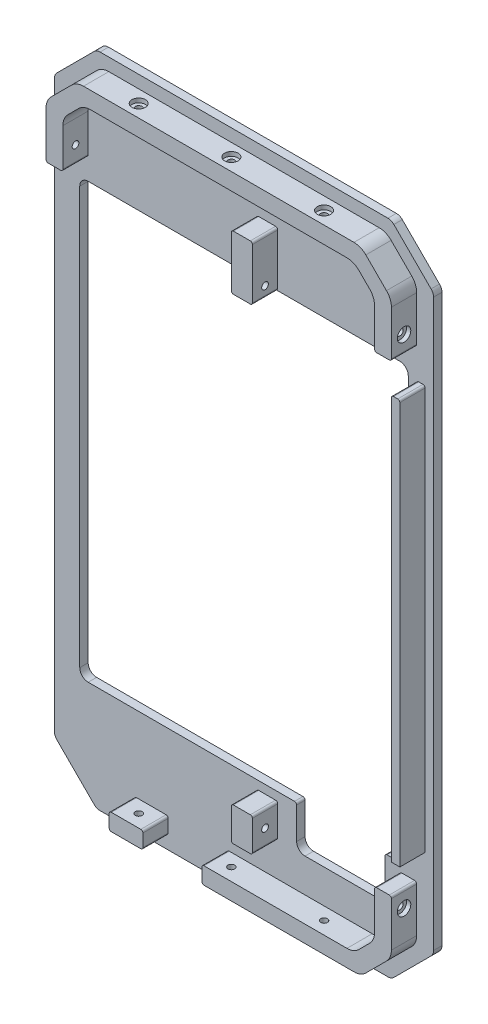
SolidWorks part; units mm, degrees
material "6061-T4 (SS)"
ref_plane "前视基准面" through (0, 0, 0) normal (0, 0, 1) x (1, 0, 0)
ref_plane "上视基准面" through (0, 0, 0) normal (0, 1, 0) x (1, 0, 0)
ref_plane "右视基准面" through (0, 0, 0) normal (1, 0, 0) x (0, 0, -1)
sketch "草图1" plane through (0, 0, 0) normal (0, 0, 1) x (1, 0, 0)
  line L1 (0, 0) -> (-90, 0)
  line L2 (0, 0) -> (0, 156)
  line L3 (0, 156) -> (-90, 156)
  line L4 (-90, 0) -> (-90, 156)
  dimension "D1" = 90
  dimension "D2" = 156
extrude "凸台-拉伸1" add sketch "草图1" along normal blind 2
chamfer "倒角1" distance 10 angle 45 4 edges at (0, 0, 1) (-90, 0, 1) (-90, 156, 1) (0, 156, 1)
sketch "草图2" plane through (0, 0, 2) normal (0, 0, 1) x (1, 0, 0)
  line L0 (-10, 156) -> (-80, 156) construction
  line L1 (-78.7574, 153) -> (-11.2426, 153)
  line L2 (-87, 144.7574) -> (-87, 11.2426)
  line L3 (-78.7574, 3) -> (-11.2426, 3)
  line L4 (-3, 144.7574) -> (-3, 11.2426)
  line L5 (-80, 0) -> (-10, 0) construction
  line L6 (-90, 146) -> (-90, 10) construction
  line L7 (0, 10) -> (0, 146) construction
  line L8 (-87, 144.7574) -> (-78.7574, 153)
  line L10 (-11.2426, 153) -> (-3, 144.7574)
  line L11 (-85, 151) -> (-82.8787, 148.8787) construction
  line L12 (-87, 11.2426) -> (-78.7574, 3)
  line L14 (-3, 11.2426) -> (-11.2426, 3)
  line L17 (-80, 156) -> (-90, 146) construction
  line L18 (-5, 151) -> (-7.1213, 148.8787) construction
  line L19 (0, 146) -> (-10, 156) construction
  line L20 (-85, 5) -> (-82.8787, 7.1213) construction
  line L21 (-90, 10) -> (-80, 0) construction
  line L22 (-5, 5) -> (-7.1213, 7.1213) construction
  line L24 (-10, 0) -> (0, 10) construction
  dimension "D1" = 3
  dimension "D2" = 3
  dimension "D3" = 3
  dimension "D4" = 3
  dimension "D5" = 3
  dimension "D6" = 3
  dimension "D7" = 3
  dimension "D8" = 3
extrude "凸台-拉伸2" add sketch "草图2" along normal blind 6
sketch "草图4" plane through (-87, 0, 0) normal (-1, 0, 0) x (0, 0, 1)
  line L2 (0, 156) -> (2, 156) construction
  line L3 (2, 0) -> (0, 0) construction
  line L4 (5, 11.2426) -> (5, 144.7574) construction
  line L5 (8, 11.2426) -> (2, 11.2426) construction
  line L6 (8, 144.7574) -> (2, 144.7574) construction
  circle A0 centre (5, 137) radius 0.8
  circle A1 centre (5, 19) radius 0.8
  point P10 (1, 0)
  dimension "D3" = 19
  dimension "D2" = 19
shell "抽壳3" thickness 4
sketch "草图5" plane through (0, 3, 0) normal (0, -1, 0) x (-1, 0, 0)
  line L0 (45, -5) -> (45, -8) construction
  line L1 (78.7574, -8) -> (11.2426, -8) construction
  circle A1 centre (67, -5) radius 0.8
  circle A2 centre (23, -5) radius 0.8
  circle A3 centre (45, -5) radius 0.8
  dimension "D1" = 22
  dimension "D2" = 22
extrude "上下盖子孔" cut sketch "草图5" against normal blind 200
sketch "草图25" plane through (0, 0, 8) normal (0, 0, 1) x (1, 0, 0)
  line L0 (-87, 144.7574) -> (-87, 11.2426) construction
  line L1 (-101.5211, 153.7054) -> (-86, 153.7054)
  line L2 (-101.5211, 153.7054) -> (-101.5211, -12.2357)
  line L3 (-101.5211, -12.2357) -> (-86, -12.2357)
  line L4 (-86, 153.7054) -> (-86, -12.2357)
  line L5 (-3, 11.2426) -> (-3, 144.7574) construction
  line L6 (30.0437, 153.7054) -> (-4, 153.7054)
  line L7 (30.0437, 153.7054) -> (30.0437, -12.2357)
  line L8 (30.0437, -12.2357) -> (-4, -12.2357)
  line L9 (-4, 153.7054) -> (-4, -12.2357)
  dimension "D1" = 1
  dimension "D2" = 1
extrude "切除-拉伸17" cut sketch "草图25" against normal blind 6
sketch "草图8" plane through (0, 0, 8) normal (0, 0, 1) x (1, 0, 0)
  line L0 (-10, 156) -> (-80, 156) construction
  line L5 (-100.9873, 133) -> (8.5404, 133)
  line L12 (-100.9873, 133) -> (-100.9873, 23)
  line L13 (-100.9873, 23) -> (8.5404, 23)
  line L14 (8.5404, 133) -> (8.5404, 23)
  line L15 (-80, 0) -> (-10, 0) construction
  dimension "D1" = 23
  dimension "D2" = 23
extrude "刀路" cut sketch "草图8" against normal blind 6
sketch "草图28" plane through (0, 0, 2) normal (0, 0, 1) x (1, 0, 0)
  line L0 (-82, 143.1005) -> (-82, 144.1005)
  line L2 (-83, 143.1005) -> (-83, 133)
  line L3 (-83, 133) -> (-82, 133)
  line L4 (-82, 143.1005) -> (-82, 133)
  line L5 (-83, 143.1005) -> (-77.1005, 149) construction
  line L6 (-82, 144.1005) -> (-83, 143.1005)
  line L7 (-8, 143.1005) -> (-8, 144.1005)
  line L8 (-7, 133) -> (-8, 133)
  line L9 (-7, 133) -> (-7, 143.1005)
  line L11 (-8, 133) -> (-8, 143.1005)
  line L12 (-12.8995, 149) -> (-7, 143.1005) construction
  line L13 (-8, 144.1005) -> (-7, 143.1005)
  line L14 (-8, 12.8995) -> (-8, 11.8995)
  line L16 (-7, 12.8995) -> (-7, 23)
  line L17 (-7, 23) -> (-8, 23)
  line L18 (-8, 12.8995) -> (-8, 23)
  line L19 (-7, 12.8995) -> (-12.8995, 7) construction
  line L20 (-8, 11.8995) -> (-7, 12.8995)
extrude "凸台-拉伸5" add sketch "草图28" along normal blind 6
fillet "外角" radius 2 8 edges at (0, 10, 1) (-10, 0, 1) (-80, 0, 1) (-90, 10, 1) (-90, 146, 1) (-80, 156, 1) (0, 146, 1) (-10, 156, 1)
fillet "外内角" radius 4 16 edges at (-78.7574, 3, 5) (-11.2426, 3, 5) (-11.2426, 153, 5) (-78.7574, 153, 5) (-86, 10.2426, 5) (-4, 10.2426, 5) (-4, 145.7574, 5) (-86, 145.7574, 5) (-77.1005, 7, 5) (-83, 12.8995, 5) (-12.8995, 7, 5) (-8, 11.8995, 5) (-8, 144.1005, 5) (-12.8995, 149, 5) (-77.1005, 149, 5) (-82, 144.1005, 5)
extrude "盖子孔" cut sketch "草图4" against normal blind 100
sketch "草图6" plane through (0, 0, 2) normal (0, 0, 1) x (1, 0, 0)
  line L0 (-90, 145.1716) -> (-90, 10.8284) construction
  line L5 (-79.1716, 0) -> (-10.8284, 0) construction
  line L10 (-10.8284, 156) -> (-79.1716, 156) construction
  line L17 (-42, 141) -> (-37, 141)
  line L18 (-42, 141) -> (-42, 128)
  line L19 (-42, 15) -> (-37, 15)
  line L20 (-37, 141) -> (-37, 128)
  line L25 (-42, 23) -> (-42, 15)
  line L26 (-42, 128) -> (-37, 128)
  line L28 (-42, 23) -> (-37, 23)
  line L30 (-37, 23) -> (-37, 15)
  dimension "D1" = 48
  dimension "D2" = 5
  dimension "D3" = 15
  dimension "D4" = 15
  dimension "D5" = 13
  dimension "D6" = 8
extrude "凸台-拉伸3" add sketch "草图6" along normal blind 6
sketch "草图17" plane through (-37, 0, 0) normal (1, 0, 0) x (0, 0, -1)
  line L0 (-5, 23) -> (-5, 15) construction
  line L1 (-8, 15) -> (-2, 15) construction
  line L2 (-8, 128) -> (-2, 128) construction
  line L3 (-8, 23) -> (-2, 23) construction
  circle A0 centre (-5, 130.5) radius 0.8
  circle A1 centre (-5, 19) radius 0.8
  dimension "D1" = 2.5
extrude "主板螺孔" cut sketch "草图17" against normal blind 10
sketch "草图10" plane through (0, 0, 8) normal (0, 0, 1) x (1, 0, 0)
  line L0 (-42, 128) -> (-37, 128) construction
  line L10 (-37, 23) -> (-42, 23) construction
  line L16 (0, 10.8284) -> (0, 145.1716) construction
  line L22 (-84, 128) -> (-6, 128)
  line L23 (-84, 128) -> (-84, 25)
  line L25 (-84, 25) -> (-6, 25)
  line L26 (-6, 128) -> (-6, 25)
  line L27 (-90, 145.1716) -> (-90, 10.8284) construction
  dimension "D1" = 6
  dimension "D2" = 6
  dimension "D3" = 2
  dimension "D4" = 0
sketch "草图11" plane through (0, 0, 8) normal (0, 0, 1) x (1, 0, 0)
  line L12 (-63, 15.8854) -> (-49, 15.8854)
  line L13 (-63, 15.8854) -> (-63, -3.0549)
  line L14 (-63, -3.0549) -> (-49, -3.0549)
  line L15 (-49, 15.8854) -> (-49, -3.0549)
  line L50 (-90, 145.1716) -> (-90, 10.8284) construction
  line L56 (-90, 33.7511) -> (-71, 33.7511)
  line L57 (-90, 33.7511) -> (-90, -5.4069)
  line L58 (-90, -5.4069) -> (-71, -5.4069)
  line L59 (-71, 33.7511) -> (-71, -5.4069)
  dimension "D1" = 8
extrude "PCI-E" cut sketch "草图11" against normal blind 6
sketch "草图14" plane through (0, 0, 0) normal (0, 0, -1) x (-1, 0, 0)
  line L0 (0, 10.8284) -> (0, 145.1716) construction
  line L1 (27, 10) -> (63, 10) construction
  line L2 (27, 10) -> (27, 146) construction
  line L3 (27, 146) -> (63, 146) construction
  line L4 (63, 10) -> (63, 146) construction
  line L5 (79.1716, 0) -> (10.8284, 0) construction
  line L6 (90, 145.1716) -> (90, 10.8284) construction
  line L7 (10.8284, 156) -> (79.1716, 156) construction
  circle A0 centre (27, 10) radius 1
  circle A1 centre (63, 10) radius 1
  circle A2 centre (27, 146) radius 1
  circle A3 centre (63, 146) radius 1
  dimension "D1" = 27
  dimension "D2" = 10
  dimension "D3" = 27
  dimension "D4" = 10
extrude "IO螺孔" [suppressed] cut sketch "草图14" against normal blind 10
extrude "IO挖空" cut sketch "草图10" against normal blind 10
sketch "草图15" plane through (0, 0, 0) normal (0, 0, -1) x (-1, 0, 0)
  line L0 (6, 25) -> (6, 128) construction
  line L5 (11.5, 25) -> (32.5, 25)
  line L6 (11.5, 25) -> (11.5, 15)
  line L8 (32.5, 25) -> (32.5, 15)
  line L11 (11.5, 15) -> (32.5, 15)
  line L12 (84, 25) -> (6, 25) construction
  dimension "D1" = 10
  dimension "D2" = 21
  dimension "D3" = 0
  dimension "D4" = 5.5
extrude "电源挖空" cut sketch "草图15" against normal blind 10
fillet "圆角3" [suppressed] radius 1
hole_wizard "打孔尺寸(%根据)内六角花形沉头螺钉的类型1" [suppressed] positions "草图18" profile "草图19" countersink size "M6" standard "GB"
sketch "草图18" [suppressed] plane through (0, 0, 0) normal (0, 0, -1) x (-1, 0, 0)
  point P0 (27, 146)
  point P3 (63, 146)
  point P6 (27, 10)
  point P9 (63, 10)
sketch "草图19" plane through (-27, 146, 0) normal (1, 0, 0) x (0, 1, 0)
  line L0 (0, 0) -> (0, 8)
  line L1 (0, 8) -> (1.1, 8)
  line L2 (1.1, 8) -> (1.1, 1.1)
  line L3 (1.1, 1.1) -> (2.2, 0)
  line L5 (2.2, 0) -> (0, 0)
  line L6 (-1.1, 1.1) -> (-2.2, 0) construction
  line L11 (0, -6.35) -> (0, 107.95) construction
  dimension "通孔孔直径" = 2.2
  dimension "通孔孔深度" = 8
  dimension "近端锥形沉头孔直径" = 4.4
  dimension "近端锥形沉头孔角度" = 90
sketch "草图21" plane through (0, 3, 0) normal (0, -1, 0) x (-1, 0, 0)
  circle A0 centre (67, -5) radius 1.6
  circle A1 centre (45, -5) radius 1.6
  circle A2 centre (23, -5) radius 1.6
extrude "切除-拉伸14" cut sketch "草图21" against normal blind 1
sketch "草图20" plane through (0, 153, 0) normal (0, 1, 0) x (1, 0, 0)
  circle A0 centre (-67, -5) radius 1.6
  circle A1 centre (-45, -5) radius 1.6
  circle A2 centre (-23, -5) radius 1.6
extrude "螺孔装饰" cut sketch "草图20" against normal blind 1
sketch "草图22" plane through (-86, 0, 0) normal (-1, 0, 0) x (0, 0, 1)
  circle A0 centre (5, 137) radius 1.6
  circle A1 centre (5, 19) radius 1.6
extrude "切除-拉伸15" cut sketch "草图22" against normal blind 1
sketch "草图23" plane through (-4, 0, 0) normal (1, 0, 0) x (0, 0, -1)
  circle A0 centre (-5, 137) radius 1.6
  circle A1 centre (-5, 19) radius 1.6
extrude "切除-拉伸16" cut sketch "草图23" against normal blind 1
sketch "草图26" plane through (0, 0, 2) normal (0, 0, 1) x (1, 0, 0)
  line L0 (0, 10.8284) -> (0, 145.1716) construction
  line L1 (-4, 126) -> (-2, 126)
  line L2 (-4, 126) -> (-4, 30)
  line L3 (-4, 30) -> (-2, 30)
  line L4 (-2, 126) -> (-2, 30)
  line L5 (-79.1716, 0) -> (-10.8284, 0) construction
  line L6 (-10.8284, 156) -> (-79.1716, 156) construction
  dimension "D1" = 2
  dimension "D2" = 2
  dimension "D3" = 30
  dimension "D4" = 30
extrude "凸台-拉伸4" add sketch "草图26" along normal blind 6
fillet "圆角5" radius 2 6 edges at (-84, 25, 1) (-32.5, 15, 1) (-11.5, 15, 1) (-6, 25, 1) (-6, 128, 1) (-84, 128, 1)
fillet "圆角7" radius 0.5 2 edges at (-11.5, 25, 1) (-32.5, 25, 1)
fillet "圆角8" radius 0.5 22 edges at (-37, 128, 5) (-42, 128, 5) (-42, 141, 5) (-37, 141, 5) (-42, 15, 5) (-42, 23, 5) (-37, 23, 5) (-37, 15, 5) (-71, 3, 5) (-71, 7, 5) (-63, 3, 5) (-63, 7, 5) (-49, 3, 5) (-49, 7, 5) (-4, 23, 5) (-8, 23, 5) (-4, 126, 5) (-2, 126, 5) (-8, 133, 5) (-4, 133, 5) (-86, 133, 5) (-82, 133, 5)
